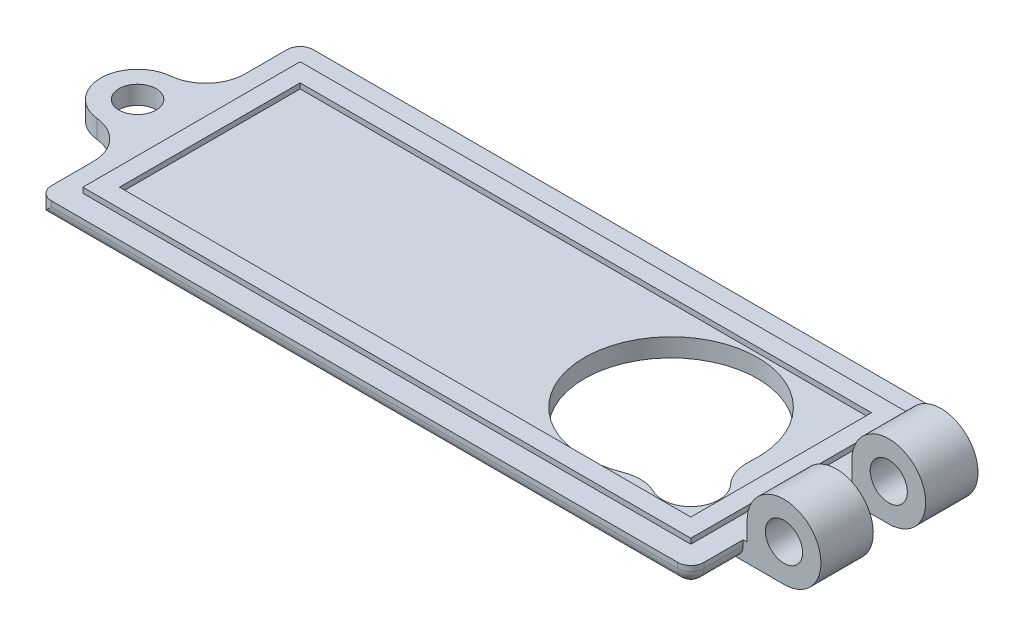
SolidWorks part; units mm, degrees
ref_plane "Front Plane" through (0, 0, 0) normal (0, 0, 1) x (1, 0, 0)
ref_plane "Top Plane" through (0, 0, 0) normal (0, 1, 0) x (1, 0, 0)
ref_plane "Right Plane" through (0, 0, 0) normal (1, 0, 0) x (0, 0, -1)
sketch "Sketch1" plane through (0, 0, 0) normal (0, 1, 0) x (1, 0, 0)
  line L1 (0, 0) -> (63.2968, 0)
  line L2 (0, 0) -> (0, 25.4)
  line L3 (0, 25.4) -> (63.2968, 25.4)
  line L4 (63.2968, 0) -> (63.2968, 25.4)
  dimension "D1" = 25.4
  dimension "D2" = 63.2968
extrude "Boss-Extrude1" add sketch "Sketch1" along normal blind 1.778
sketch "Sketch2" plane through (0, 1.778, 0) normal (0, 1, 0) x (1, 0, 0)
  line L4 (59.3598, 21.463) -> (3.937, 21.463)
  line L5 (3.937, 21.463) -> (3.937, 3.937)
  line L6 (3.937, 3.937) -> (59.3598, 3.937)
  line L7 (59.3598, 3.937) -> (59.3598, 21.463)
  line L8 (2.159, 23.241) -> (2.159, 2.159)
  line L9 (2.159, 2.159) -> (61.1378, 2.159)
  line L10 (61.1378, 2.159) -> (61.1378, 23.241)
  line L11 (61.1378, 23.241) -> (2.159, 23.241)
  line L12 (2.159, 23.241) -> (2.159, 2.159)
  line L13 (2.159, 2.159) -> (61.1378, 2.159)
  line L14 (61.1378, 2.159) -> (61.1378, 23.241)
  line L15 (61.1378, 23.241) -> (2.159, 23.241)
  dimension "D1" = 2.159
  dimension "D2" = 1.778
extrude "Boss-Extrude2" add sketch "Sketch2" along normal blind 0.508
sketch "Sketch3" plane through (0, 0, 0) normal (0, -1, 0) x (1, 0, 0)
  line L0 (63.2968, 0) -> (63.2968, -25.4) construction
  line L1 (63.2968, -25.4) -> (0, -25.4) construction
  line L2 (0, 0) -> (63.2968, 0) construction
  circle A0 centre (48.6791, -12.7) radius 6.6167 construction
  arc A1 (51.7878, -4.9021) -> (57.0454, -12.0103) centre (48.6791, -12.7) ccw
  circle A2 centre (56.0451, -7.2517) radius 1.4605 construction
  arc A3 (58.0479, -9.1076) -> (54.8568, -4.7933) centre (56.0451, -7.2517) ccw
  circle A4 centre (56.0451, -7.2517) radius 2.7305 construction
  circle A5 centre (48.6791, -12.7) radius 8.3947 construction
  arc A6 (58.0479, -9.1076) -> (57.0454, -12.0103) centre (60.8425, -11.6972) ccw
  arc A7 (54.8568, -4.7933) -> (51.7878, -4.9021) centre (53.1988, -1.363) cw
  dimension "D2" = 13.2334
  dimension "D3" = 12.7
  dimension "D5" = 2.921
  dimension "D6" = 7.2517
  dimension "D7" = 7.2517
  dimension "D8" = 1.27
  dimension "D9" = 3.81
  dimension "D1" = 14.6177
  dimension "D4" = 1.778
extrude "Cut-Extrude1" cut sketch "Sketch3" against normal through all
sketch "Sketch4" plane through (0, 0, 0) normal (0, 0, 1) x (1, 0, 0)
  line L2 (67.2592, 3.5814) -> (63.6778, 3.5814) construction
  line L3 (63.2968, 1.778) -> (63.2968, 0) construction
  line L4 (63.6778, 3.5814) -> (63.6778, 1.778)
  line L5 (63.6778, 1.778) -> (63.2968, 1.778)
  line L6 (63.2968, 0) -> (67.2592, 0)
  circle A0 centre (67.2592, 3.5814) radius 1.8034
  arc A1 (67.2592, 0) -> (63.6778, 3.5814) centre (67.2592, 3.5814) ccw
  circle A3 centre (67.2592, 3.5814) radius 3.5814 construction
  line M8 (63.2968, 0) -> (63.2968, 1.778)
  dimension "D2" = 3.6068
  dimension "D3" = 0.381
  dimension "D1" = 1.778
extrude "Boss-Extrude3" add sketch "Sketch4" against normal up to surface (25.4 mm away) contours L6 A1 L4 L5 A0 M8 up to face at (31.6484, 0.889, -25.4)
sketch "Sketch5" plane through (0, 1.778, 0) normal (0, 1, 0) x (1, 0, 0)
  line L0 (70.8406, 0) -> (70.8406, 25.4) construction
  line L1 (63.2968, 25.4) -> (70.8406, 25.4)
  line L2 (63.2968, 25.4) -> (63.2968, 20.32)
  line L3 (63.2968, 20.32) -> (70.8406, 20.32)
  line L4 (70.8406, 25.4) -> (70.8406, 20.32)
  line L5 (63.2968, 15.24) -> (63.2968, 10.16)
  line L6 (63.2968, 15.24) -> (70.8406, 15.24)
  line L7 (70.8406, 15.24) -> (70.8406, 10.16)
  line L8 (63.2968, 10.16) -> (70.8406, 10.16)
  line L9 (63.2968, 5.08) -> (63.2968, 0)
  line L10 (63.2968, 5.08) -> (70.8406, 5.08)
  line L11 (70.8406, 5.08) -> (70.8406, 0)
  line L12 (63.2968, 0) -> (70.8406, 0)
  line L13 (63.6778, 0) -> (70.8406, 0) construction
  line L14 (63.6778, 25.4) -> (0, 25.4) construction
  line L15 (63.6778, 25.4) -> (63.6778, 0) construction
  dimension "D2" = 5.08
  dimension "D3" = 0.381
  dimension "D1" = 3
extrude "Cut-Extrude2" cut sketch "Sketch5" against normal through all both and the other way through all
ref_plane "Plane1" through (31.6484, 0, 0) normal (1, 0, 0) x (0, 0, -1)
sketch "Sketch6" plane through (0, 1.778, 0) normal (0, 1, 0) x (1, 0, 0)
  line L0 (0, 25.4) -> (0, 0) construction
  line L1 (0, 16.2814) -> (0, 9.1186)
  line L2 (-3.0734, 16.2814) -> (0, 16.2814)
  line L3 (-3.0734, 9.1186) -> (0, 9.1186)
  line L4 (-3.0734, 12.7) -> (-1.27, 12.7) construction
  circle A0 centre (-3.0734, 12.7) radius 1.8034
  arc A1 (-3.0734, 16.2814) -> (-3.0734, 9.1186) centre (-3.0734, 12.7) ccw
  circle A2 centre (-3.0734, 12.7) radius 3.5814 construction
  point P7 (0, 12.7)
  dimension "D2" = 3.6068
  dimension "D3" = 1.27
  dimension "D1" = 1.778
extrude "Boss-Extrude4" add sketch "Sketch6" against normal up to surface (1.778 mm away) up to face at (54.0681, 0, -12.7)
fillet "Fillet1" radius 3.81 2 edges at (0, 0.889, -9.1186) (0, 0.889, -16.2814)
fillet "Fillet2" radius 1.27 9 edges at (63.2968, 0.889, 0) (63.2968, 0.889, -25.4) (0, 0.889, -25.4) (31.6484, 0, -25.4) (63.2968, 0, -22.86) (63.2968, 0, -12.7) (63.2968, 0, -2.54) (0, 0.889, 0) (31.6484, 0, 0)
